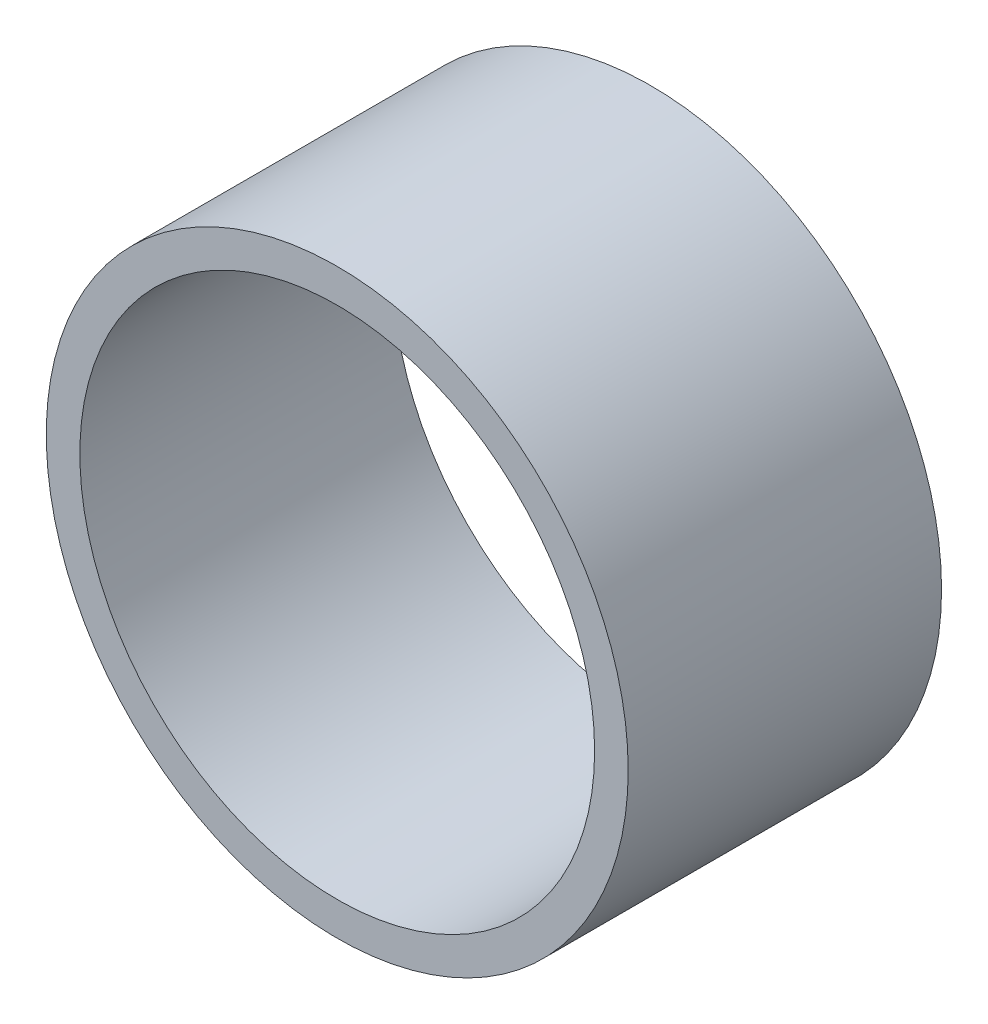
SolidWorks part; units mm, degrees
ref_plane "Front" through (0, 0, 0) normal (0, 0, 1) x (1, 0, 0)
ref_plane "Top" through (0, 0, 0) normal (0, 1, 0) x (1, 0, 0)
ref_plane "Right" through (0, 0, 0) normal (1, 0, 0) x (0, 0, -1)
sketch "Esquisse1" plane through (0, 0, 0) normal (0, 0, 1) x (1, 0, 0)
  circle A0 centre (0, 0) radius 23
  circle A1 centre (0, 0) radius 26
  dimension "D1" = 46
  dimension "D2" = 52
extrude "Boss.-Extru.1" add sketch "Esquisse1" along normal blind 28
